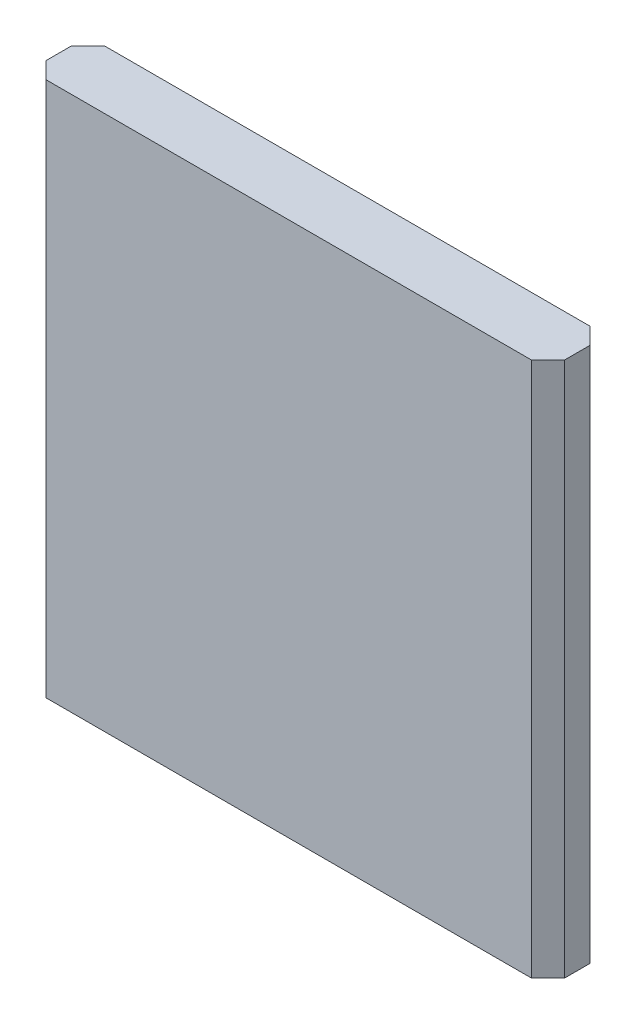
SolidWorks part; units mm, degrees
ref_plane "Plano frontal" through (0, 0, 0) normal (0, 0, 1) x (1, 0, 0)
ref_plane "Plano superior" through (0, 0, 0) normal (0, 1, 0) x (1, 0, 0)
ref_plane "Plano direito" through (0, 0, 0) normal (1, 0, 0) x (0, 0, -1)
sketch "Esboço1" plane through (0, 0, 0) normal (0, 0, 1) x (1, 0, 0)
  line L1 (-45, -30) -> (-355, -30)
  line L2 (-45, -30) -> (-45, -350)
  line L3 (-45, -350) -> (-355, -350)
  line L4 (-355, -30) -> (-355, -350)
extrude "Ressalto-extrusão1" add sketch "Esboço1" along normal blind 35
chamfer "Chanfro1" distance 10 angle 45 4 edges at (-45, -190, 35) (-355, -190, 0) (-355, -190, 35) (-45, -190, 0)
